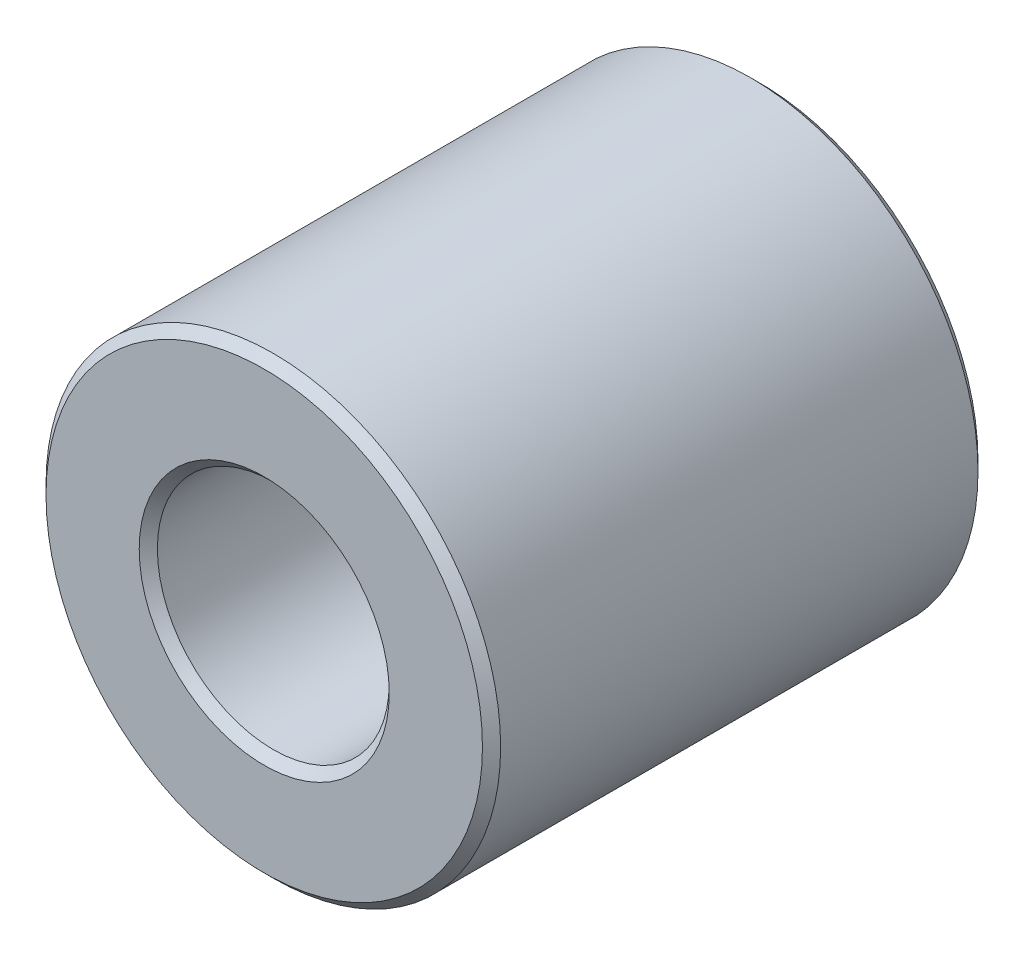
SolidWorks part; units mm, degrees
material "6061-T6 (SS)"
ref_plane "Front Plane" through (0, 0, 0) normal (0, 0, 1) x (1, 0, 0)
ref_plane "Top Plane" through (0, 0, 0) normal (0, 1, 0) x (1, 0, 0)
ref_plane "Right Plane" through (0, 0, 0) normal (1, 0, 0) x (0, 0, -1)
sketch "Sketch1" plane through (0, 0, 0) normal (0, 0, 1) x (1, 0, 0)
  circle A0 centre (0, 0) radius 2.55
  circle A1 centre (0, 0) radius 5
  dimension "D1" = 5.1
  dimension "D2" = 10
extrude "Boss-Extrude1" add sketch "Sketch1" along normal blind 10.9
chamfer "Chamfer1" distance 0.2 angle 45 4 edges at (5, 0, 0) (2.55, 0, 0) (2.55, 0, 10.9) (5, 0, 10.9)
